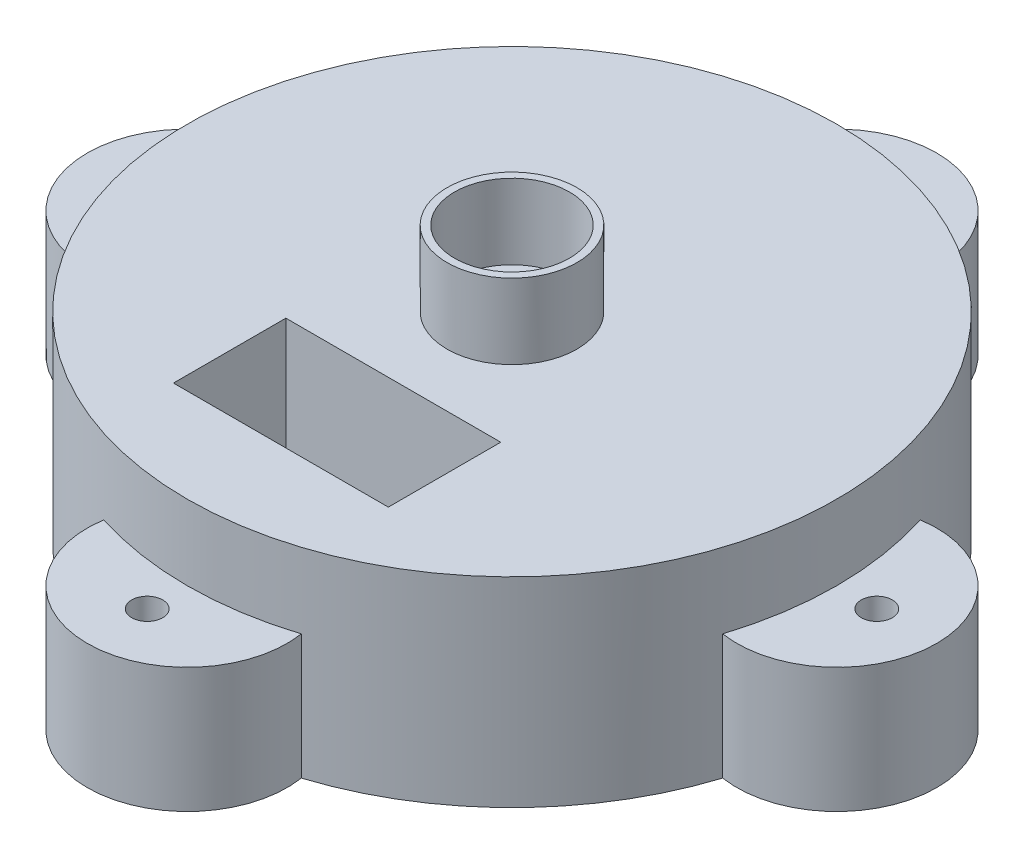
SolidWorks part; units mm, degrees
ref_plane "Front Plane" through (0, 0, 0) normal (0, 0, 1) x (1, 0, 0)
ref_plane "Top Plane" through (0, 0, 0) normal (0, 1, 0) x (1, 0, 0)
ref_plane "Right Plane" through (0, 0, 0) normal (1, 0, 0) x (0, 0, -1)
sketch "Sketch2" plane through (0, 0, 0) normal (0, 1, 0) x (1, 0, 0)
  circle A0 centre (0, 0) radius 65
  dimension "D1" = 130
extrude "Boss-Extrude1" add sketch "Sketch2" along normal blind 40
sketch "Sketch4" plane through (0, 40, 0) normal (0, -1, 0) x (1, 0, 0)
  line L1 (21.5, 23.75) -> (-21.5, 23.75)
  line L2 (21.5, 23.75) -> (21.5, 46.25)
  line L3 (21.5, 46.25) -> (-21.5, 46.25)
  line L4 (-21.5, 23.75) -> (-21.5, 46.25)
  line L5 (21.5, 23.75) -> (-21.5, 46.25) construction
  line L6 (21.5, 46.25) -> (-21.5, 23.75) construction
  point P0 (0, 35)
  dimension "D1" = 22.5
  dimension "D2" = 43
  dimension "D3" = 35
extrude "Cut-Extrude1" cut sketch "Sketch4" along normal blind 38
sketch "Sketch5" plane through (-21.5, 0, 62.75) normal (-1, 0, 0) x (0, 0, 1)
  line L6 (-19.2167, 7.326) -> (-34.2167, 7.326)
  line L7 (-19.2167, 7.326) -> (-19.2167, 12.326)
  line L8 (-19.2167, 12.326) -> (-34.2167, 12.326)
  line L9 (-34.2167, 7.326) -> (-34.2167, 12.326)
  line L10 (-19.2167, 7.326) -> (-34.2167, 12.326) construction
  line L11 (-19.2167, 12.326) -> (-34.2167, 7.326) construction
  point P0 (-62.75, 32)
  point P1 (-26.7167, 9.826)
  point P5 (-25.6383, 12.3566)
  point P8 (-26.7167, 9.826)
  dimension "D1" = 15
  dimension "D2" = 5
sketch "Sketch6" plane through (0, 0, 0) normal (0, 1, 0) x (1, 0, 0)
  line L4 (-0.0001, -55) -> (-0.0001, -73) construction
  circle A2 centre (0, 0) radius 65 construction
  circle A3 centre (-0.0001, -73) radius 3.1
  arc A6 (-61.9231, 19.762) -> (-61.9231, -19.7618) centre (-65, 0.0001) ccw
  circle A8 centre (0, 0) radius 65
  circle A10 centre (0, 0) radius 65
  circle A12 centre (-73, 0.0001) radius 3.1
  arc A14 (-19.762, -61.9231) -> (19.7618, -61.9231) centre (-0.0001, -65) ccw
  arc A15 (19.762, 61.9231) -> (-19.7618, 61.9231) centre (0.0001, 65) ccw
  circle A16 centre (0.0001, 73) radius 3.1
  arc A17 (61.9231, -19.762) -> (61.9231, 19.7618) centre (65, -0.0001) ccw
  circle A18 centre (73, -0.0001) radius 3.1
  point P5 (-0.0001, -65)
  point P30 (0, 0)
  point P35 (0.4878, -1.815)
  dimension "D1" = 40
  dimension "D2" = 6.2
  dimension "D5" = 8
  dimension "D3" = 0
  dimension "D4" = 4
extrude "Boss-Extrude2" add sketch "Sketch6" along normal blind 25
sketch "Sketch9" plane through (0, 40, 0) normal (0, -1, 0) x (-1, 0, 0)
  circle A0 centre (0, 0) radius 13
  circle A2 centre (0, 0) radius 11.5
  dimension "D1" = 23
  dimension "23" = 26
extrude "Boss-Extrude3" add sketch "Sketch9" against normal blind 15
extrude "Cut-Extrude2" cut sketch "Sketch5" along normal blind 60
